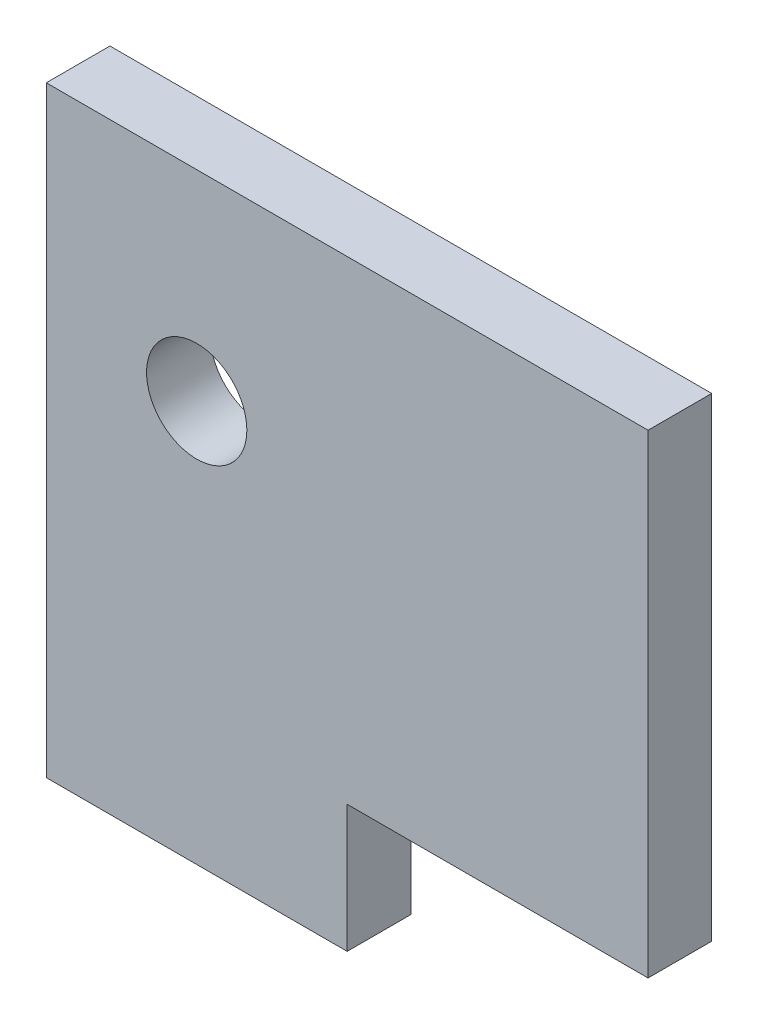
SolidWorks part; units mm, degrees
ref_plane "Front Plane" through (0, 0, 0) normal (0, 0, 1) x (1, 0, 0)
ref_plane "Top Plane" through (0, 0, 0) normal (0, 1, 0) x (1, 0, 0)
ref_plane "Right Plane" through (0, 0, 0) normal (1, 0, 0) x (0, 0, -1)
sketch "Sketch1" plane through (0, 0, 0) normal (0, 0, 1) x (1, 0, 0)
  line L0 (15, 0) -> (15, 6.35)
  line L1 (0, 0) -> (15, 0)
  line L2 (0, 0) -> (0, 30)
  line L3 (0, 30) -> (30, 30)
  line L4 (30, 6.35) -> (30, 30)
  line L5 (15, 6.35) -> (30, 6.35)
  line L7 (15, 6.35) -> (0, 20) construction
  line L8 (7.5, 13.175) -> (7.5, 20) construction
  line L9 (7.5, 20) -> (0, 20) construction
  circle A0 centre (7.5, 20) radius 2.5
  point P3 (0, 0)
  point P13 (0, 0)
  dimension "D5" = 5
  dimension "D1" = 30
  dimension "D2" = 30
  dimension "D3" = 15
  dimension "D4" = 6.35
  dimension "D6" = 10
  dimension "D7" = 7.5
extrude "Boss-Extrude1" add sketch "Sketch1" along normal blind 3.175
